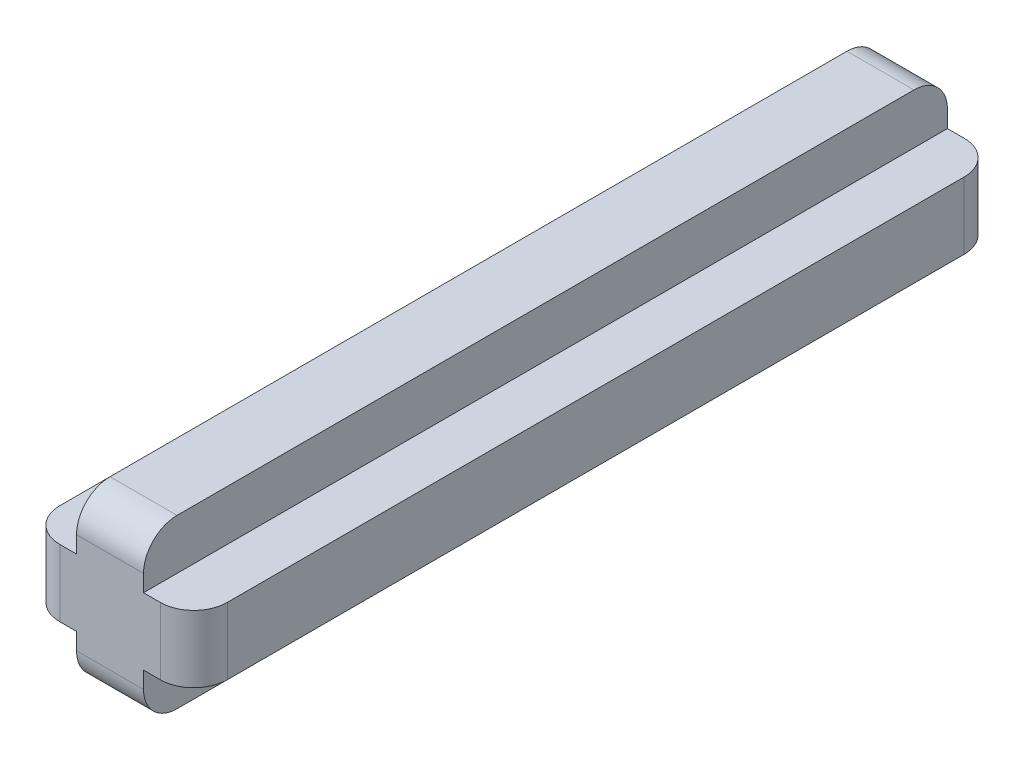
SolidWorks part; units mm, degrees
material "PVC 0.007 Plasticized"
ref_plane "Front Plane" through (0, 0, 0) normal (0, 0, 1) x (1, 0, 0)
ref_plane "Top Plane" through (0, 0, 0) normal (0, 1, 0) x (1, 0, 0)
ref_plane "Right Plane" through (0, 0, 0) normal (1, 0, 0) x (0, 0, -1)
sketch "Sketch1" plane through (0, 0, 0) normal (0, 0, 1) x (1, 0, 0)
  line L0 (0, 0) -> (0, 5)
  line L1 (0, 5) -> (5, 5)
  line L2 (5, 5) -> (5, 0)
  line L3 (5, 0) -> (0, 0)
extrude "Boss-Extrude1" add sketch "Sketch1" along normal blind 24
sketch "Sketch2" plane through (0, 0, 24) normal (0, 0, 1) x (1, 0, 0)
  line L0 (2.5, -1.275) -> (2.5, 6.9366) construction
  line L1 (5.7735, 2.5) -> (-1.1721, 2.5) construction
  line L2 (5, 3.5) -> (5, 1.5)
  line L3 (2.5, 5.0011) -> (3.5, 5)
  line L4 (5, 1.5) -> (3.5, 1.5)
  line L5 (5, 5) -> (0, 5) construction
  line L6 (3.5, 5) -> (3.5, 3.5)
  line L7 (3.5, 1.5) -> (3.5, 0)
  line L8 (3.5, 3.5) -> (5, 3.5)
  line L9 (5, 0) -> (5, 5) construction
  line L10 (0, 0) -> (5, 0) construction
  line L11 (2.5, 0) -> (1.5, 0)
  line L12 (1.5, 0) -> (1.5, 1.5)
  line L13 (1.5, 1.5) -> (0, 1.5)
  line L14 (0, 5) -> (0, 0) construction
  line L15 (0, 3.5) -> (0, 2.5)
  line L16 (0, 3.5) -> (1.5, 3.5)
  line L17 (1.5, 3.5) -> (1.5, 5)
  line L18 (1.5, 5) -> (2.5, 5.0011)
  line L19 (2.5, 0) -> (3.5, 0)
  line L20 (0, 2.5) -> (0, 1.5)
  line L21 (3.5, 5) -> (3.5, 6.7286)
  line L22 (3.5, 6.7286) -> (5.7735, 6.7286)
  line L23 (5.7735, 6.7286) -> (5.7735, 3.5)
  line L24 (5.7735, 3.5) -> (5, 3.5)
  line L25 (5, 1.5) -> (5.6673, 1.5)
  line L26 (5.6673, 1.5) -> (5.6673, -0.7828)
  line L27 (5.6673, -0.7828) -> (3.5, -0.7828)
  line L28 (3.5, -0.7828) -> (3.5, 0)
  line L29 (1.5, 0) -> (1.5, -0.934)
  line L30 (1.5, -0.934) -> (-0.906, -0.934)
  line L31 (-0.906, -0.934) -> (-0.906, 1.5)
  line L32 (-0.906, 1.5) -> (0, 1.5)
  line L33 (0, 3.5) -> (0, 5)
  line L34 (0, 5) -> (1.5, 5)
  line M16 (0, 0) -> (5, 0)
  line M17 (5, 0) -> (5, 5)
  line M18 (5, 5) -> (0, 5)
  line M19 (0, 5) -> (0, 0)
  dimension "D1" = 1
  dimension "D2" = 1
  dimension "D4" = 2
  dimension "D5" = 2
extrude "Cut-Extrude1" cut sketch "Sketch2" against normal through all contours L16 L17 M18 M19 | L6 L8 M17 M18 | L4 L7 M16 M17 | L12 L13 M19 M16
sketch "Sketch3" plane through (0, 5, 0) normal (0, 1, 0) x (-1, 0, 0)
  line L1 (-3.5, 0) -> (-3.5, 24) construction
  line L2 (-3.5, 13) -> (-1.5, 13)
  line L3 (-1.5, 0) -> (-1.5, 24) construction
  line L4 (-1.5, 13) -> (-1.5, 11.5)
  line L5 (-1.5, 0) -> (-1.5, 24) construction
  line L6 (-1.5, 11.5) -> (-3.5, 11.5)
  line L7 (-3.5, 0) -> (-3.5, 24) construction
  line L8 (-3.5, 11.5) -> (-3.5, 13)
sketch "Sketch4" plane through (0, 3.5, 0) normal (0, 1, 0) x (-1, 0, 0)
  line L0 (-8.2056, 8) -> (4.3717, 8) construction
sketch "Sketch5" plane through (5, 0, 0) normal (1, 0, 0) x (0, 0, -1)
  line L0 (-24, 1.5) -> (-13, 1.5)
  line L1 (0, 1.5) -> (-24, 1.5) construction
  line L2 (-13, 1.5) -> (-13, 3.5)
  line L3 (0, 3.5) -> (-24, 3.5) construction
  line L4 (-13, 3.5) -> (-11.5, 3.5)
  line L5 (-11.5, 3.5) -> (-11.5, 1.5)
  line L6 (-11.5, 1.5) -> (-13, 1.5)
  dimension "D1" = 1.5
sketch "Sketch6" plane through (0, 0, 0) normal (0, -1, 0) x (1, 0, 0)
  line L0 (3.5, 24) -> (3.5, 13)
  line L1 (3.5, 0) -> (3.5, 24) construction
  line L2 (3.5, 13) -> (1.5, 13)
  line L3 (1.5, 0) -> (1.5, 24) construction
  line L4 (1.5, 13) -> (1.5, 11.5)
  line L5 (1.5, 11.5) -> (3.5, 11.5)
  line L6 (3.5, 11.5) -> (3.5, 13)
sketch "Sketch7" plane through (0, 0, 0) normal (-1, 0, 0) x (0, 0, 1)
  line L0 (24, 3.5) -> (13, 3.5)
  line L1 (0, 3.5) -> (24, 3.5) construction
  line L2 (13, 3.5) -> (13, 1.5)
  line L3 (0, 1.5) -> (24, 1.5) construction
  line L4 (13, 1.5) -> (11.5, 1.5)
  line L5 (11.5, 1.5) -> (11.5, 3.5)
  line L6 (11.5, 3.5) -> (13, 3.5)
fillet "Fillet1" radius 1 4 edges at (0, 2.5, 24) (2.5, 0, 24) (5, 2.5, 24) (2.5, 5, 24)
sketch "Sketch8" plane through (0, 5, 0) normal (0, 1, 0) x (-1, 0, 0)
  line L0 (-1.5, 0) -> (-1.5, 23) construction
  point P0 (-1.5, 7.6096)
  point P1 (-2.3113, 18.7763)
ref_plane "Plane1" through (0, 0, 7.6096) normal (0, 0, -1) x (-1, 0, 0)
fillet "Fillet2" radius 1 4 edges at (2.5, 5, 0) (0, 2.5, 0) (2.5, 0, 0) (5, 2.5, 0)
